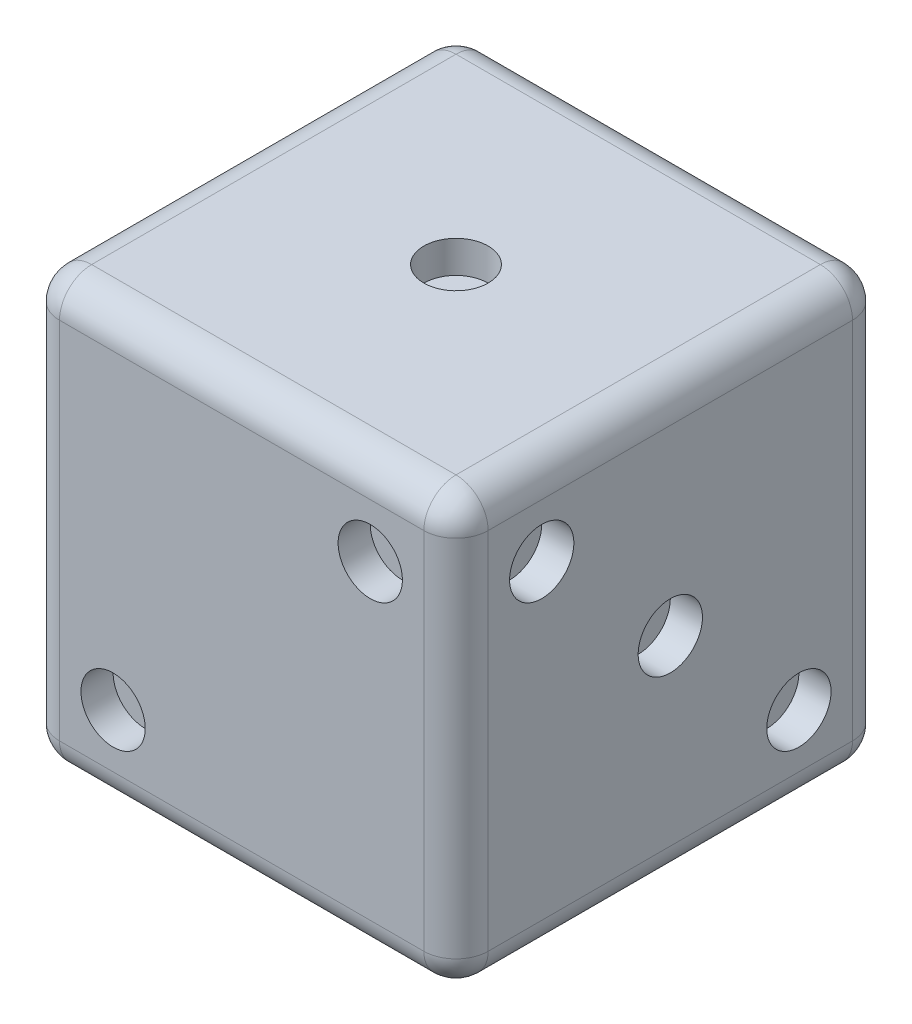
SolidWorks part; units mm, degrees
ref_plane "前视基准面" through (0, 0, 0) normal (0, 0, 1) x (1, 0, 0)
ref_plane "上视基准面" through (0, 0, 0) normal (0, 1, 0) x (1, 0, 0)
ref_plane "右视基准面" through (0, 0, 0) normal (1, 0, 0) x (0, 0, -1)
ref_plane "基准面1" through (0, 0, -10) normal (0, 0, 1) x (1, 0, 0)
sketch "草图1" plane through (0, 0, -10) normal (0, 0, 1) x (1, 0, 0)
  line L0 (-10, -10) -> (10, -10)
  line L1 (10, -10) -> (10, 10)
  line L2 (10, 10) -> (-10, 10)
  line L3 (-10, 10) -> (-10, -10)
extrude "凸台-拉伸1" add sketch "草图1" along normal blind 20
fillet "圆角1" radius 1.5 12 edges at (-10, 0, -10) (0, -10, -10) (10, 0, -10) (0, 10, -10) (-10, 0, 10) (0, -10, 10) (10, 0, 10) (0, 10, 10) (-10, 10, 0) (10, 10, 0) (10, -10, 0) (-10, -10, 0)
ref_plane "基准面2" through (0, 10, 0) normal (0, 1, 0) x (1, 0, 0)
sketch "草图2" plane through (0, 10, 0) normal (0, 1, 0) x (1, 0, 0)
  circle A0 centre (0, 0) radius 1.5
extrude "切除-拉伸1" cut sketch "草图2" against normal blind 1.5
ref_plane "基准面3" through (0, -10, 0) normal (0, 1, 0) x (1, 0, 0)
sketch "草图3" plane through (0, -10, 0) normal (0, 1, 0) x (1, 0, 0)
  circle A0 centre (-3, 6) radius 1.5
  circle A1 centre (-3, 0) radius 1.5
  circle A2 centre (-3, -6) radius 1.5
  circle A3 centre (3, 6) radius 1.5
  circle A4 centre (3, 0) radius 1.5
  circle A5 centre (3, -6) radius 1.5
extrude "切除-拉伸2" cut sketch "草图3" along normal blind 1.5
ref_plane "基准面4" through (0, 0, 10) normal (0, 0, 1) x (1, 0, 0)
sketch "草图4" plane through (0, 0, 10) normal (0, 0, 1) x (1, 0, 0)
  circle A0 centre (-6, -6) radius 1.5
  circle A1 centre (6, 6) radius 1.5
extrude "切除-拉伸3" cut sketch "草图4" against normal blind 1.5
sketch "草图5" plane through (0, 0, -10) normal (0, 0, 1) x (1, 0, 0)
  circle A0 centre (-6, -6) radius 1.5
  circle A1 centre (6, -6) radius 1.5
  circle A2 centre (0, 0) radius 1.5
  circle A3 centre (-6, 6) radius 1.5
  circle A4 centre (6, 6) radius 1.5
extrude "切除-拉伸4" cut sketch "草图5" along normal blind 1.5
ref_plane "基准面5" through (10, 0, 0) normal (1, 0, 0) x (0, 0, -1)
sketch "草图6" plane through (10, 0, 0) normal (1, 0, 0) x (0, 0, -1)
  circle A0 centre (6, -6) radius 1.5
  circle A1 centre (0, 0) radius 1.5
  circle A2 centre (-6, 6) radius 1.5
extrude "切除-拉伸5" cut sketch "草图6" against normal blind 1.5
ref_plane "基准面6" through (-10, 0, 0) normal (1, 0, 0) x (0, 0, -1)
sketch "草图7" plane through (-10, 0, 0) normal (1, 0, 0) x (0, 0, -1)
  circle A0 centre (6, -6) radius 1.5
  circle A1 centre (-6, -6) radius 1.5
  circle A2 centre (6, 6) radius 1.5
  circle A3 centre (-6, 6) radius 1.5
extrude "切除-拉伸6" cut sketch "草图7" along normal blind 1.5
